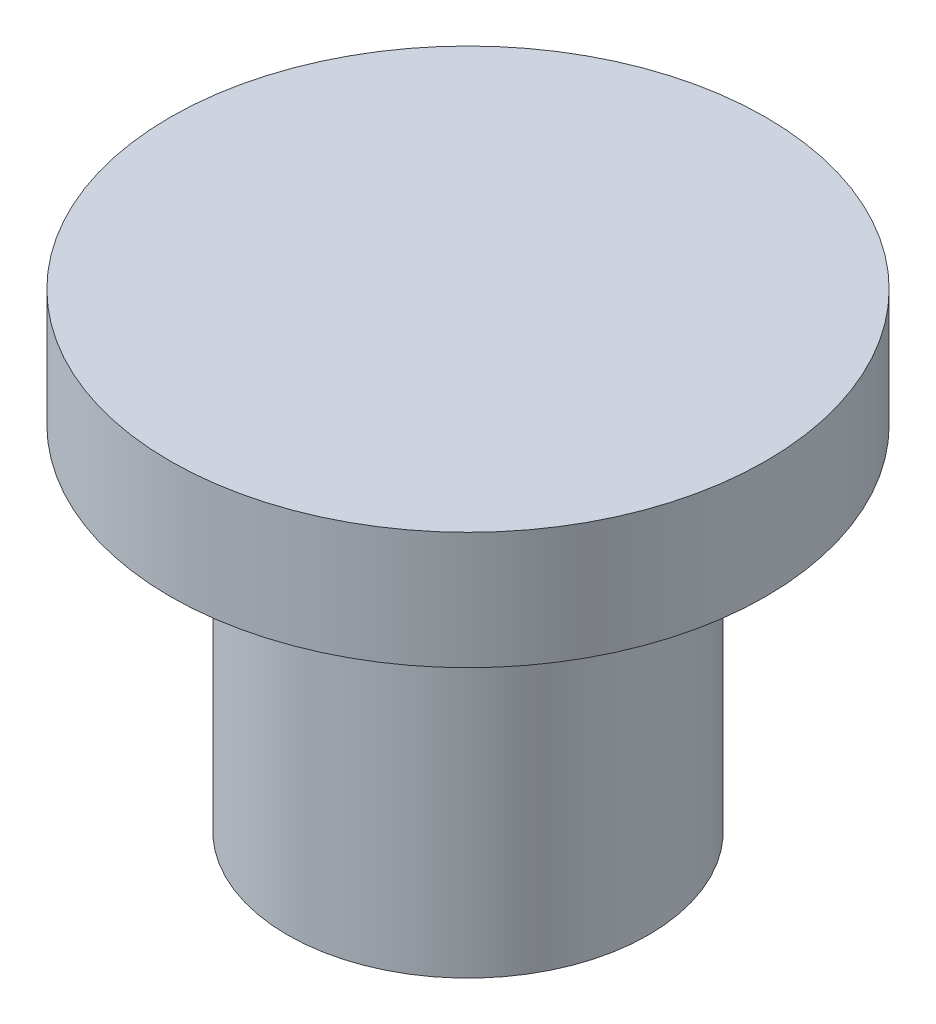
SolidWorks part; units mm, degrees
material "Barra Redonda SAE 1020 -  1\""
ref_plane "Plano frontal" through (0, 0, 0) normal (0, 0, 1) x (1, 0, 0)
ref_plane "Plano superior" through (0, 0, 0) normal (0, 1, 0) x (1, 0, 0)
ref_plane "Plano direito" through (0, 0, 0) normal (1, 0, 0) x (0, 0, -1)
sketch "Esboço2" plane through (0, 0, 0) normal (0, 0, 1) x (1, 0, 0)
  line L0 (0, 0) -> (0, 89.4177) construction
  line L1 (0, 0) -> (12.7, 0)
  line L2 (0, 20) -> (0, 0)
  line L3 (0, 20) -> (12.7, 20)
  line L4 (12.7, 0) -> (12.7, 20)
  dimension "D1" = 25.4
  dimension "D2" = 20
revolve "Revolução2" add sketch "Esboço2" angle 360 about L0
sketch "Esboço3" plane through (0, 0, 0) normal (0, 0, 1) x (1, 0, 0)
  line L0 (-12.7, 0) -> (12.7, 0) construction
  line L1 (7.7, 0) -> (12.7, 0)
  line L2 (7.7, 0) -> (7.7, 15)
  line L3 (7.7, 15) -> (12.7, 15)
  line L4 (12.7, 0) -> (12.7, 15)
  line L5 (12.7, 0) -> (12.7, 20) construction
  line L6 (0, 0) -> (0, 42.7075) construction
  dimension "D1" = 5
  dimension "D2" = 15
revolve "Corte-Revolução1" cut sketch "Esboço3" angle 360 about L6
